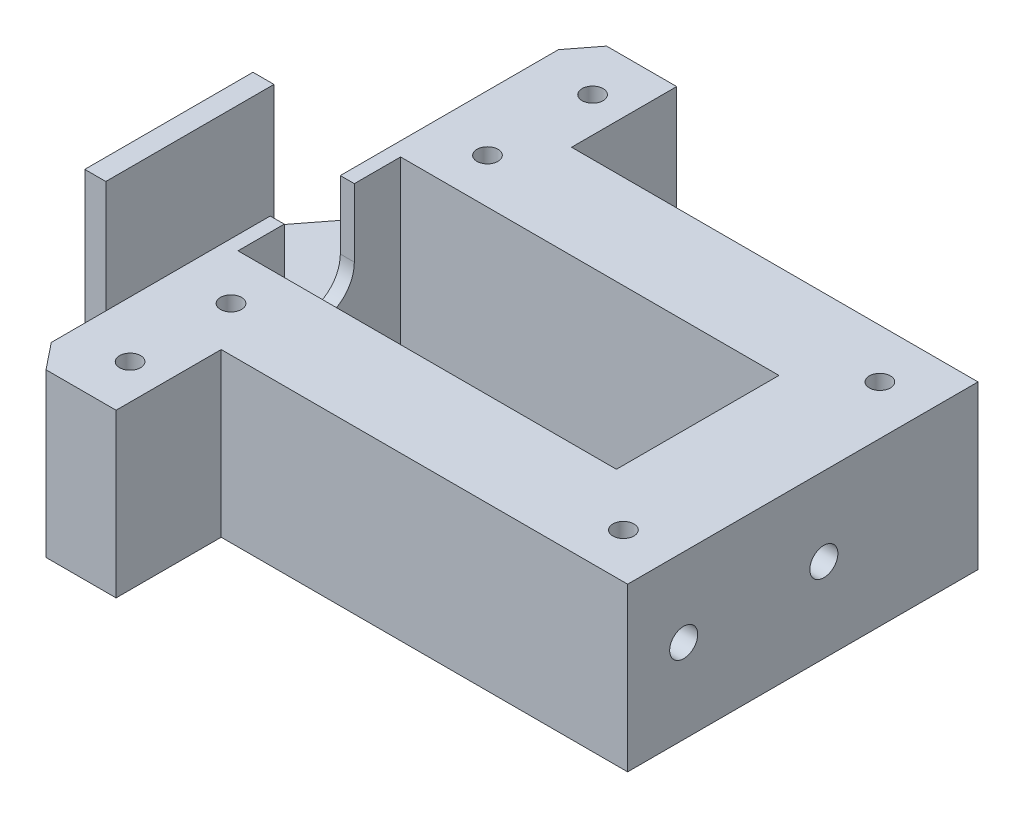
SolidWorks part; units mm, degrees
material "6061 Alloy"
ref_plane "Front Plane" through (0, 0, 0) normal (0, 0, 1) x (1, 0, 0)
ref_plane "Top Plane" through (0, 0, 0) normal (0, 1, 0) x (1, 0, 0)
ref_plane "Right Plane" through (0, 0, 0) normal (1, 0, 0) x (0, 0, -1)
sketch "Sketch2" plane through (0, 0, 0) normal (0, 1, 0) x (1, 0, 0)
  line L0 (0, 5.767) -> (0, -6.233)
  line L1 (0, -6.233) -> (11, -20)
  line L2 (11, -20) -> (45, -20)
  line L3 (45, -20) -> (45, 20)
  line L4 (45, 20) -> (11, 20)
  line L5 (11, 20) -> (0, 5.767)
  point P0 (45, 0)
  dimension "D1" = 12
  dimension "D2" = 11
  dimension "D3" = 40
  dimension "D4" = 45
  dimension "D5" = 13.767
extrude "Boss-Extrude1" add sketch "Sketch2" along normal blind 11.6
sketch "Sketch3" plane through (0, 11.6, 0) normal (0, 1, 0) x (1, 0, 0)
  line L0 (1.5, 7.7079) -> (1.5, -8.1103)
  line L1 (11, 20) -> (0, 5.767) construction
  line L2 (0, -6.233) -> (11, -20) construction
  line L3 (1.5, -8.1103) -> (9.5, -18.1227)
  line L4 (9.5, -18.1227) -> (9.5, 18.0591)
  line L5 (9.5, 18.0591) -> (1.5, 7.7079)
  line L6 (0, 5.767) -> (0, -6.233) construction
  dimension "D1" = 1.5
  dimension "D2" = 8
extrude "Cut-Extrude1" cut sketch "Sketch3" against normal blind 9.55
sketch "Sketch5" plane through (0, 11.6, 0) normal (0, 1, 0) x (1, 0, 0)
  line L0 (9.5, -18.1227) -> (9.5, 18.0591) construction
  line L1 (10.5, 5.8) -> (37.5, 5.8)
  line L2 (10.5, 5.8) -> (10.5, -5.8)
  line L3 (10.5, -5.8) -> (37.5, -5.8)
  line L4 (37.5, 5.8) -> (37.5, -5.8)
  point P4 (10.5, 0)
  dimension "D1" = 11.6
  dimension "D2" = 27
  dimension "D3" = 1
extrude "Cut-Extrude3" cut sketch "Sketch5" against normal through all
sketch "Sketch6" plane through (10.5, 0, 0) normal (1, 0, 0) x (0, 0, -1)
  line L0 (5.8, 0) -> (-5.8, 0) construction
  line L1 (2.5, 6.75) -> (2.5, 11.6)
  line L2 (5.8, 11.6) -> (-5.8, 11.6) construction
  line L3 (2.5, 11.6) -> (-2.5, 11.6)
  line L4 (-2.5, 11.6) -> (-2.5, 6.75)
  arc A0 (-2.5, 6.75) -> (2.5, 6.75) centre (0, 6.75) ccw
  point P5 (0, 0)
  dimension "D2" = 5
  dimension "D1" = 6.75
extrude "Cut-Extrude4" cut sketch "Sketch6" against normal blind 3
sketch "Sketch7" plane through (0, 11.6, 0) normal (0, 1, 0) x (1, 0, 0)
  line L0 (1.5, 7.7079) -> (0, 5.767)
  line L1 (0, 5.767) -> (1.5, 5.767)
  line L2 (1.5, 7.7079) -> (1.5, -8.1103) construction
  line L3 (1.5, 5.767) -> (1.5, 7.7079)
  line L4 (0, -6.233) -> (1.5, -6.233)
  line L5 (1.5, 7.7079) -> (1.5, -8.1103) construction
  line L6 (1.5, -6.233) -> (1.5, -8.1103)
  line L7 (1.5, -8.1103) -> (0, -6.233)
extrude "Cut-Extrude5" cut sketch "Sketch7" against normal up to surface (9.55 mm away) up to face at (5.5, 2.05, 0.1165)
sketch "Sketch8" plane through (0, 0, 0) normal (0, -1, 0) x (1, 0, 0)
  line L0 (37.5, 5.8) -> (37.5, -5.8) construction
  line L1 (10.5, 5.8) -> (37.5, 5.8) construction
  line L2 (37.5, -5.8) -> (10.5, -5.8) construction
  circle A0 centre (30.5, 9.89) radius 1.26
  circle A1 centre (30.5, -9.89) radius 1.26
  dimension "D4" = 2.52
  dimension "D1" = 7
  dimension "D2" = 4.09
  dimension "D3" = 4.09
extrude "Cut-Extrude6" cut sketch "Sketch8" against normal blind 4
sketch "Sketch9" plane through (0, 0, 0) normal (0, -1, 0) x (1, 0, 0)
  line L0 (11, 20) -> (45, 20) construction
  line L1 (16, 20) -> (45, 20)
  line L2 (16, 20) -> (16, 12.5)
  line L3 (16, 12.5) -> (45, 12.5)
  line L4 (45, 20) -> (45, 12.5)
  line L5 (45, 20) -> (45, -20) construction
  line L6 (45, -20) -> (11, -20) construction
  line L7 (16, -20) -> (45, -20)
  line L8 (16, -20) -> (16, -12.5)
  line L9 (16, -12.5) -> (45, -12.5)
  line L10 (45, -20) -> (45, -12.5)
  dimension "D1" = 7.5
  dimension "D2" = 7.5
  dimension "D3" = 5
extrude "Cut-Extrude7" cut sketch "Sketch9" against normal through all
sketch "Sketch10" plane through (0, 11.6, 0) normal (0, 1, 0) x (1, 0, 0)
  line L0 (16, 12.5) -> (16, 20) construction
  line L1 (45, 12.5) -> (16, 12.5) construction
  line L2 (10.5, -5.8) -> (37.5, -5.8) construction
  line L3 (45, -12.5) -> (45, 12.5) construction
  line L4 (11, -20) -> (16, -20) construction
  line L5 (16, 20) -> (11, 20) construction
  circle A0 centre (13.5, 16.5) radius 0.75
  circle A1 centre (13.5, 9) radius 0.75
  circle A2 centre (41.5, 9) radius 0.75
  circle A3 centre (41.5, -9.3) radius 0.75
  circle A4 centre (13.5, -9.3) radius 0.75
  circle A5 centre (13.5, -16.5) radius 0.75
  dimension "D7" = 1.5
  dimension "D1" = 2.5
  dimension "D2" = 3.5
  dimension "D3" = 3.5
  dimension "D4" = 3.5
  dimension "D5" = 3.5
  dimension "D6" = 3.5
extrude "Cut-Extrude8" cut sketch "Sketch10" against normal blind 4
sketch "Sketch11" plane through (45, 0, 0) normal (1, 0, 0) x (0, 0, -1)
  line L0 (-12.5, 0) -> (12.5, 0) construction
  line L1 (-20, 11.6) -> (-20, 0) construction
  circle A0 centre (-8.5, 6) radius 1
  circle A1 centre (1.5, 6) radius 1
  dimension "D3" = 2
  dimension "D1" = 10
  dimension "D2" = 11.5
  dimension "D4" = 6
extrude "Cut-Extrude9" cut sketch "Sketch11" against normal blind 4
